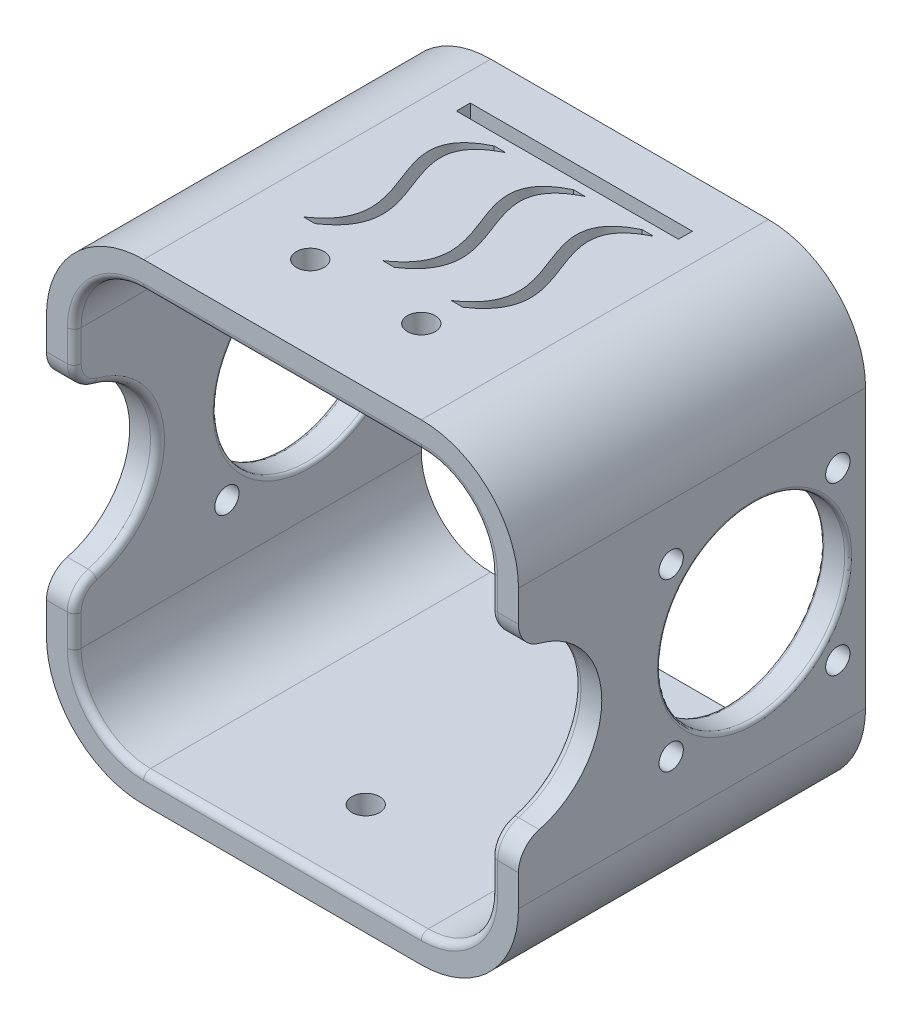
SolidWorks part; units mm, degrees
ref_plane "Piano frontale" through (0, 0, 0) normal (0, 0, 1) x (1, 0, 0)
ref_plane "Piano superiore" through (0, 0, 0) normal (0, 1, 0) x (1, 0, 0)
ref_plane "Piano destro" through (0, 0, 0) normal (1, 0, 0) x (0, 0, -1)
sketch "Schizzo1" plane through (0, 0, 0) normal (0, 0, 1) x (1, 0, 0)
  line L0 (-10, 0) -> (-50, 0)
  line L1 (0, -10) -> (0, -50)
  line L2 (-60, -10) -> (-60, -50)
  line L3 (-50, -60) -> (-10, -60)
  arc A0 (0, -50) -> (-10, -60) centre (-10, -50) cw
  arc A1 (-50, -60) -> (-60, -50) centre (-50, -50) cw
  arc A2 (0, -10) -> (-10, 0) centre (-10, -10) ccw
  arc A3 (-60, -10) -> (-50, 0) centre (-50, -10) cw
  point P7 (0, -60)
  point P10 (-60, -60)
  point P13 (0, 0)
  point P16 (-60, 0)
  dimension "D4" = 10
  dimension "D1" = 60
  dimension "D2" = 60
  dimension "D3" = 60
extrude "Estrusione-Sottile1" add sketch "Schizzo1" along normal blind 50 thin
sketch "Schizzo2" plane through (0, 4, 0) normal (0, 1, 0) x (1, 0, 0)
  line L0 (-30, 0) -> (-30, -50) construction
  line L1 (-10, 0) -> (-50, 0) construction
  line L2 (-10, -50) -> (-50, -50) construction
  circle A0 centre (-38, -38) radius 2
  circle A1 centre (-22, -38) radius 2
  dimension "D5" = 4
  dimension "D6" = 4
  dimension "D1" = 8
  dimension "D2" = 8
  dimension "D3" = 12
  dimension "D4" = 12
extrude "Taglio-Estrusione1" cut sketch "Schizzo2" against normal blind 10
sketch "Schizzo3" plane through (-64, 0, 0) normal (-1, 0, 0) x (0, 0, 1)
  line L0 (50, -10) -> (50, -50) construction
  circle A0 centre (50, -30) radius 12
  dimension "D1" = 24
extrude "Taglio-Estrusione2" cut sketch "Schizzo3" along direction (-1, 0, 0) on the side against the normal up to surface (68 mm away)
fillet "Raccordo1" radius 4 1 edges at (-62, -18, 50)
fillet "Raccordo2" radius 4 1 edges at (-62, -42, 50)
fillet "Raccordo3" radius 4 1 edges at (2, -18, 50)
fillet "Raccordo4" radius 4 1 edges at (2, -42, 50)
sketch "Schizzo4" plane through (0, -64, 0) normal (0, -1, 0) x (1, 0, 0)
  line L0 (-30, 50) -> (-30, 0) construction
  line L1 (-50, 50) -> (-10, 50) construction
  line L2 (-50, 0) -> (-10, 0) construction
  circle A0 centre (-30, 38) radius 2
  dimension "D1" = 4
  dimension "D2" = 12
extrude "Taglio-Estrusione3" cut sketch "Schizzo4" against normal blind 10
sketch "Schizzo5" plane through (0, 4, 0) normal (0, 1, 0) x (1, 0, 0)
  line L0 (-30, 0) -> (-30, -50) construction
  line L1 (-46, -6.9458) -> (-14, -6.9458)
  line L2 (-46, -6.9458) -> (-46, -8.9458)
  line L3 (-46, -8.9458) -> (-14, -8.9458)
  line L4 (-14, -6.9458) -> (-14, -8.9458)
  line L5 (-10, 0) -> (-50, 0) construction
  line L6 (-10, -50) -> (-50, -50) construction
  line L7 (-30.9605, -32.9287) -> (-32.6391, -32.9195)
  line L8 (-26.0641, -10.3322) -> (-27.7428, -10.3231)
  line L9 (-42.1357, -33.1817) -> (-43.8144, -33.1725)
  line L10 (-37.2394, -10.5852) -> (-38.918, -10.576)
  line L11 (-21.0473, -32.9631) -> (-22.7259, -32.9539)
  line L12 (-16.1509, -10.3666) -> (-17.8296, -10.3574)
  spline S0 degree 3 poles (-16.1509, -10.3666) (-27.5731, -15.9557) (-10.2901, -25.7029) (-21.0473, -32.9631) knots 0 0 0 0 1 1 1 1
  spline S1 degree 3 poles (-17.8296, -10.3574) (-29.2518, -15.9465) (-11.9688, -25.6937) (-22.7259, -32.9539) knots 0 0 0 0 1 1 1 1
  spline S2 degree 3 poles (-26.0641, -10.3322) (-37.4863, -15.9213) (-20.2033, -25.6686) (-30.9605, -32.9287) knots 0 0 0 0 1 1 1 1
  spline S3 degree 3 poles (-27.7428, -10.3231) (-39.1649, -15.9122) (-21.882, -25.6594) (-32.6391, -32.9195) knots 0 0 0 0 1 1 1 1
  spline S4 degree 3 poles (-37.2394, -10.5852) (-48.6615, -16.1743) (-31.3786, -25.9215) (-42.1357, -33.1817) knots 0 0 0 0 1 1 1 1
  spline S5 degree 3 poles (-38.918, -10.576) (-50.3402, -16.1651) (-33.0573, -25.9123) (-43.8144, -33.1725) knots 0 0 0 0 1 1 1 1
  dimension "D1" = 16
  dimension "D2" = 16
  dimension "D3" = 2
extrude "Taglio-Estrusione4" cut sketch "Schizzo5" against normal blind 10
sketch "Schizzo7" plane through (-64, 0, 0) normal (-1, 0, 0) x (0, 0, 1)
  line L0 (0, -30) -> (38, -30) construction
  line L1 (0, -10) -> (0, -50) construction
  line L2 (0, -18) -> (47.951, -18) construction
  line L3 (0, -42) -> (47.951, -42) construction
  line L4 (16, -18) -> (16, -42) construction
  arc A0 (47, -18.381) -> (47, -41.619) centre (50, -30) ccw construction
  arc A1 (47, -18.381) -> (50, -14.5081) centre (46, -14.5081) ccw construction
  arc A2 (50, -45.4919) -> (47, -41.619) centre (46, -45.4919) ccw construction
  circle A3 centre (28, -18) radius 1.75
  circle A4 centre (28, -42) radius 1.75
  circle A5 centre (4, -42) radius 1.75
  circle A6 centre (4, -18) radius 1.75
  dimension "D4" = 3.5
  dimension "D1" = 12
  dimension "D2" = 12
  dimension "D3" = 16
  dimension "D5" = 12
extrude "Taglio-Estrusione5" cut sketch "Schizzo7" against normal up to surface (68 mm away) up to face at (4, -30, 35.7906)
sketch "Schizzo8" plane through (-64, 0, 0) normal (-1, 0, 0) x (0, 0, 1)
  circle A0 centre (16, -30) radius 13.5
  dimension "D1" = 27
extrude "Taglio-Estrusione6" cut sketch "Schizzo8" against normal up to surface (68 mm away) up to face at (4, -19.75, 4)
fillet "Raccordo5" radius 0.5 1 edges at (-64, -43.5, 16)
fillet "Raccordo6" radius 0.5 1 edges at (-60, -16.5, 16)
fillet "Raccordo7" radius 0.5 1 edges at (4, -43.5, 16)
fillet "Raccordo8" radius 0.5 1 edges at (0, -43.5, 16)
fillet "Raccordo9" radius 1 16 edges at (0, -43.0424, 49.1623) (-2.9289, -57.0711, 50) (0, -47.746, 50) (-2.9289, -2.9289, 50) (-30, 0, 50) (-57.0711, -2.9289, 50) (-60, -12.254, 50) (-57.0711, -57.0711, 50) (-30, -60, 50) (-60, -16.9576, 49.1623) (-60, -30, 38) (-60, -47.746, 50) (-60, -43.0424, 49.1623) (0, -30, 38) (0, -12.254, 50) (0, -16.9576, 49.1623)
